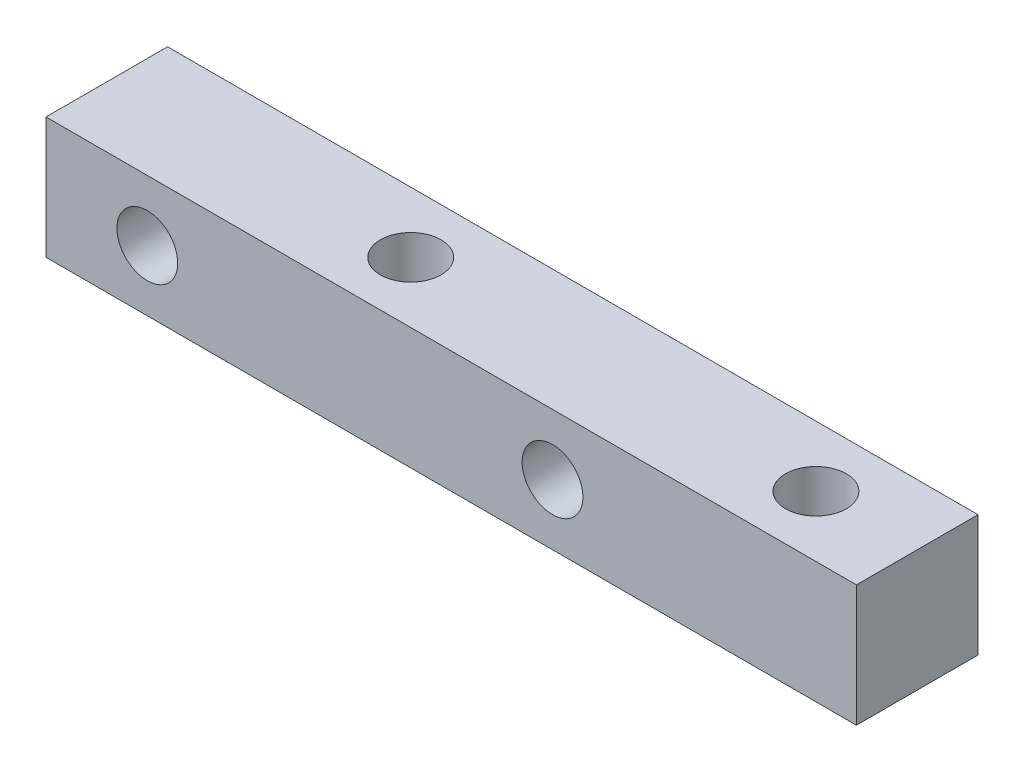
SolidWorks part; units mm, degrees
ref_plane "前视基准面" through (0, 0, 0) normal (0, 0, 1) x (1, 0, 0)
ref_plane "上视基准面" through (0, 0, 0) normal (0, 1, 0) x (1, 0, 0)
ref_plane "右视基准面" through (0, 0, 0) normal (1, 0, 0) x (0, 0, -1)
sketch "草图1" plane through (0, 0, 0) normal (0, 0, 1) x (1, 0, 0)
  line L1 (-20, 3) -> (20, 3)
  line L2 (-20, 3) -> (-20, -3)
  line L3 (-20, -3) -> (20, -3)
  line L4 (20, 3) -> (20, -3)
  line L5 (-20, 3) -> (20, -3) construction
  line L6 (-20, -3) -> (20, 3) construction
  point P0 (0, 0)
  dimension "D1" = 6
  dimension "D2" = 40
extrude "凸台-拉伸1" add sketch "草图1" along normal blind 6
sketch "草图2" plane through (0, 0, 6) normal (0, 0, 1) x (1, 0, 0)
  line L0 (-3.1376, 0) -> (4.5378, 0) construction
  line L1 (-20, 3) -> (-20, -3) construction
  circle A0 centre (-15, 0) radius 1.5
  circle A1 centre (5, 0) radius 1.5
  dimension "D1" = 3
  dimension "D2" = 20
  dimension "D3" = 5
extrude "切除-拉伸1" cut sketch "草图2" against normal blind 6
sketch "草图3" plane through (0, 3, 0) normal (0, 1, 0) x (1, 0, 0)
  line L0 (-20, -3) -> (20, -3) construction
  line L1 (-20, -6) -> (-20, 0) construction
  line L2 (20, -6) -> (20, 0) construction
  circle A0 centre (15, -3) radius 1.5
  circle A1 centre (-5, -3) radius 1.5
  point P10 (10.185, -3)
  point P11 (-4.5795, -3)
  point P12 (16.1924, -3)
  dimension "D2" = 3
  dimension "D3" = 3
  dimension "D1" = 20
  dimension "D4" = 5
extrude "切除-拉伸2" cut sketch "草图3" against normal blind 6
